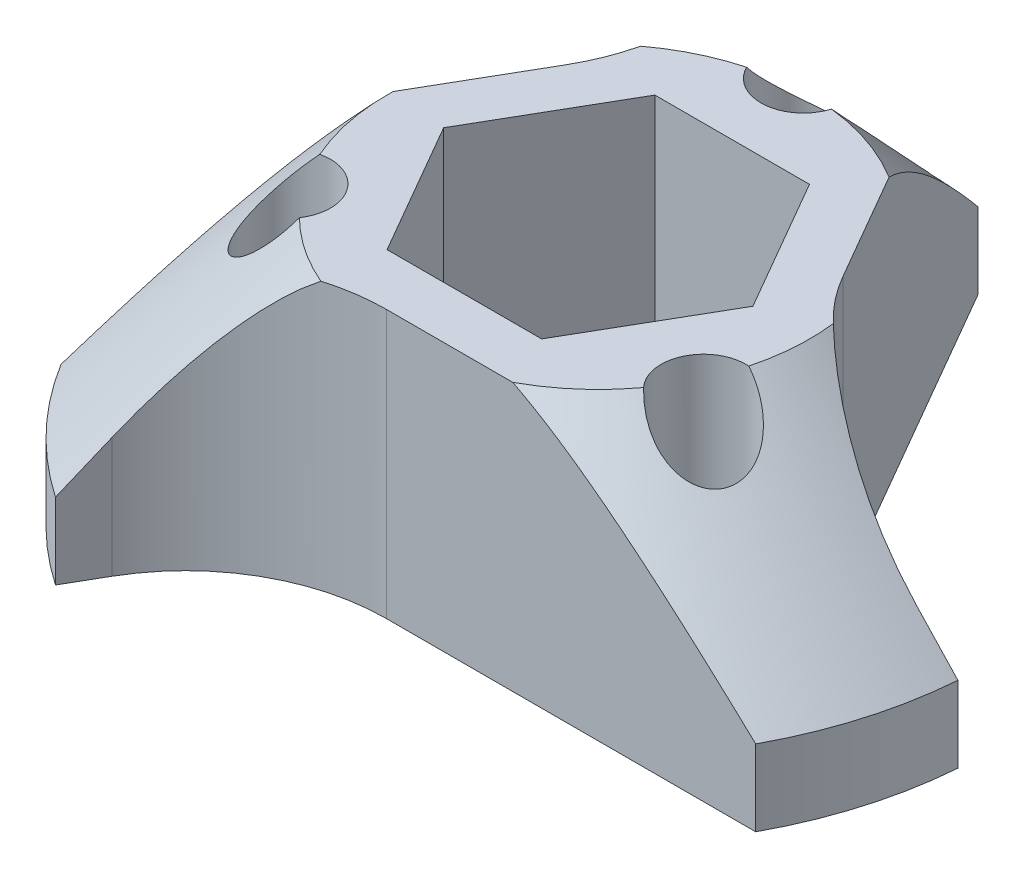
SolidWorks part; units mm, degrees
ref_plane "Front Plane" through (0, 0, 0) normal (0, 0, 1) x (1, 0, 0)
ref_plane "Top Plane" through (0, 0, 0) normal (0, 1, 0) x (1, 0, 0)
ref_plane "Right Plane" through (0, 0, 0) normal (1, 0, 0) x (0, 0, -1)
sketch "Sketch1" plane through (0, 0, 0) normal (0, 1, 0) x (1, 0, 0)
  line L0 (0, 16.6667) -> (-0.4774, 17.4935)
  line L1 (0, 16.6667) -> (-14.4338, -8.3333)
  line L2 (-14.4338, -8.3333) -> (14.4338, -8.3333)
  line L3 (14.4338, -8.3333) -> (0, 16.6667)
  line L4 (0, 2.6667) -> (-2.3094, -1.3333) construction
  line L5 (-2.3094, -1.3333) -> (2.3094, -1.3333) construction
  line L6 (2.3094, -1.3333) -> (0, 2.6667) construction
  line L7 (0, 2.6667) -> (-7.5699, 15.7781)
  circle A0 centre (0, 0) radius 8.3333 construction
  circle A1 centre (0, 0) radius 1.3333 construction
  circle A2 centre (0, 0) radius 17.5
  arc A3 (-6.6395, 5.1667) -> (-6.6395, 14.1667) centre (-14.4338, 9.6667) ccw
  circle A4 centre (0, 0) radius 1.9
  dimension "D3" = 35
  dimension "D4" = 9
  dimension "D5" = 3.8
  dimension "D1" = 25
  dimension "D2" = 7
extrude "Boss-Extrude1" add sketch "Sketch1" along normal blind 12
pattern_circular "CirPattern1" count 3 over 360 about axis through (0, 0, 0) along (0, 1, 0) of "Boss-Extrude1"
sketch "Sketch3" plane through (0, 12, 0) normal (0, 1, 0) x (1, 0, 0)
  line L1 (3.4641, 6) -> (-3.4641, 6)
  line L2 (-3.4641, 6) -> (-6.9282, 0)
  line L3 (-6.9282, 0) -> (-3.4641, -6)
  line L4 (-3.4641, -6) -> (3.4641, -6)
  line L5 (3.4641, -6) -> (6.9282, 0)
  line L6 (6.9282, 0) -> (3.4641, 6)
  circle A0 centre (0, 0) radius 6 construction
  dimension "D1" = 12
extrude "Cut-Extrude1" cut sketch "Sketch3" against normal offset from surface (9 mm away) 3 up to face at (0, 0, 0)
sketch "Sketch4" plane through (0, 12, 0) normal (0, 1, 0) x (1, 0, 0)
  line L0 (-7.1047, 14.9724) -> (-1.0425, 18.4724) construction
  line L1 (-4.0736, 16.7224) -> (-0.78, 9.9695) construction
  line L2 (7.7942, 3.1667) -> (-0.4774, 17.4935) construction
  line L3 (-6.6395, 14.1667) -> (-7.5699, 15.7781) construction
  circle A0 centre (0, 0) radius 10 construction
  circle A1 centre (-0.78, 9.9695) radius 1.9
  point P7 (0, 0)
  point P9 (0.1278, 16.4452)
  point P12 (-7.0438, 14.8668)
  point P15 (-0.8086, 9.9673)
  point P16 (-8.3575, 17.1423)
  dimension "D2" = 3.8
  dimension "D1" = 86
  dimension "D3" = 10
extrude "Cut-Extrude2" cut sketch "Sketch4" against normal up to surface (12 mm away) contours A1 up to face at (0, 0, 0)
pattern_circular "CirPattern2" count 3 over 360 about axis through (0, 0, 0) along (0, 1, 0) of "Cut-Extrude2"
sketch "Sketch5" plane through (0, 0, 0) normal (0, 0, 1) x (1, 0, 0)
  line L0 (17.8846, 3) -> (9.4703, 12)
  line L1 (-1.1547, 12) -> (15.3885, 12) construction
  line L2 (9.4703, 12) -> (17.8846, 12)
  line L3 (17.8846, 12) -> (17.8846, 3)
  line L4 (0, 0) -> (0, 14.9469) construction
  point P10 (17.4491, 0)
  point P11 (17.4491, 12)
  point P12 (17.8828, 12)
  point P13 (17.4491, 0)
  point P15 (13.8002, 12)
  point P16 (17.5207, 0)
  point P17 (8.3168, 12)
  point P18 (17.9566, 3.058)
  point P19 (9.4703, 12)
  point P20 (17.8846, 2.2721)
  dimension "D1" = 3
revolve "Cut-Revolve2" cut sketch "Sketch5" angle 360 about L4
